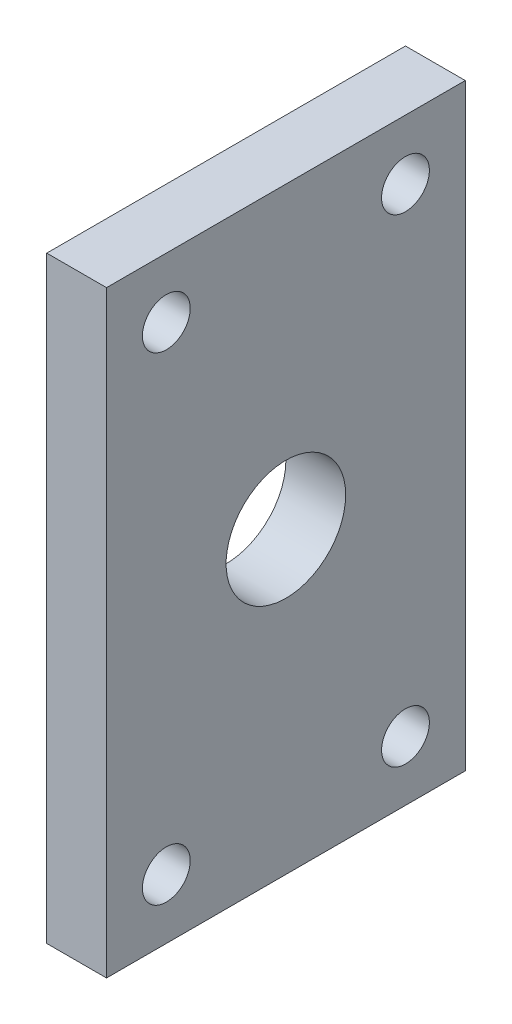
SolidWorks part; units mm, degrees
ref_plane "Front Plane" through (0, 0, 0) normal (1, 0, 0) x (0, 1, 0)
ref_plane "Top Plane" through (0, 0, 0) normal (0, 0, 1) x (0, 1, 0)
ref_plane "Right Plane" through (0, 0, 0) normal (0, 1, 0) x (-1, 0, 0)
sketch "Sketch1" plane through (0, 0, 0) normal (1, 0, 0) x (0, 1, 0)
  line L1 (0, 0) -> (100, 0)
  line L2 (0, 0) -> (0, 60)
  line L3 (0, 60) -> (100, 60)
  line L4 (100, 0) -> (100, 60)
extrude "Boss-Extrude1" add sketch "Sketch1" along normal blind 10
sketch "Sketch2" plane through (0, 0, 0) normal (1, 0, 0) x (0, 1, 0)
  circle A0 centre (10, 10) radius 4
  circle A1 centre (90, 10) radius 4
  circle A2 centre (10, 50) radius 4
  circle A3 centre (90, 50) radius 4
extrude "Cut-Extrude2" cut sketch "Sketch2" along normal through all
sketch "Sketch3" plane through (0, 0, 0) normal (1, 0, 0) x (0, 1, 0)
  circle A0 centre (50, 30) radius 10
extrude "Cut-Extrude4" cut sketch "Sketch3" along normal through all
